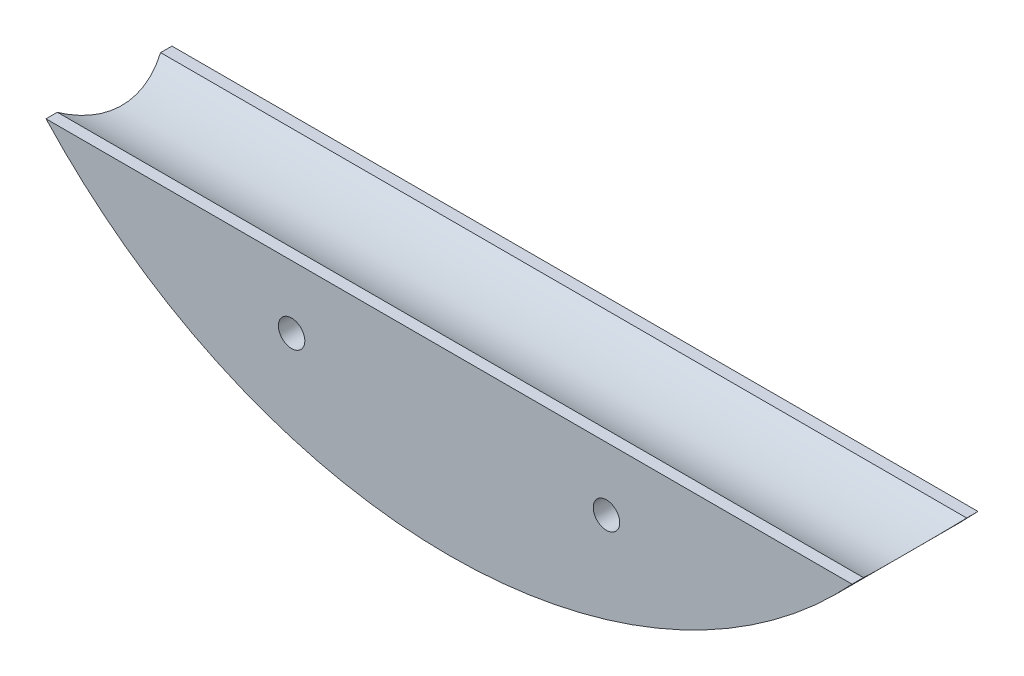
SolidWorks part; units mm, degrees
material "3.3320 (EN-AW 5019)"
ref_plane "Спереди" through (0, 0, 0) normal (0, 0, 1) x (1, 0, 0)
ref_plane "Сверху" through (0, 0, 0) normal (0, 1, 0) x (1, 0, 0)
ref_plane "Справа" through (0, 0, 0) normal (1, 0, 0) x (0, 0, -1)
sketch "Эскиз1" plane through (0, 0, 0) normal (0, 0, 1) x (1, 0, 0)
  line L0 (0, 0) -> (128, 0)
  arc A0 (0, 0) -> (128, 0) centre (64, 59) ccw
  point P4 (64, 59)
  dimension "D1" = 128
  dimension "D2" = 59
extrude "Бобышка-Вытянуть1" add sketch "Эскиз1" along normal blind 20
sketch "Эскиз2" plane through (0, 0, 0) normal (1, 0, 0) x (0, 0, -1)
  line L0 (-20, 0) -> (0, 0) construction
  circle A0 centre (-10, 14.6) radius 16.7451
  point P3 (-10, 14.6)
  point P4 (-1.8, 0)
  dimension "D1" = 14.6
  dimension "D2" = 1.8
extrude "Вырез-Вытянуть1" cut sketch "Эскиз2" along normal through all
hole_wizard "Отверстие обработанное метчиком M5x0.82" positions "Эскиз4" profile "Эскиз3" tap size "M5x0.8" standard "Ansi Metric"
sketch "Эскиз4" plane through (0, 0, 20) normal (0, 0, 1) x (1, 0, 0)
  line L0 (128, 0) -> (0, 0) construction
  point P0 (39, -10)
  point P3 (64, 0)
  dimension "D1" = 10
  dimension "D2" = 25
sketch "Эскиз3" plane through (39, -10, 20) normal (1, 0, 0) x (0, -1, 0)
  line L0 (0, 0) -> (0, 10.7618)
  line L1 (0, 10.7618) -> (2.1, 9.5)
  line L2 (2.1, 9.5) -> (2.1, 0)
  line L5 (2.1, 0) -> (0, 0)
  line L10 (0, 10.7618) -> (-2.1, 9.5) construction
  line L11 (0, -6.35) -> (0, 107.95) construction
  dimension "Диаметр сверла" = 4.2
  dimension "Глубина сверла" = 9.5
  dimension "Угол заточки сверла" = 118
cosmetic thread "Отверстие резьбы5" parameters "D1"=9.5, "D2"=5
hole_wizard "Отверстие обработанное метчиком M5x0.81" positions "Эскиз6" profile "Эскиз5" tap size "M5x0.8" standard "Ansi Metric"
sketch "Эскиз6" plane through (0, 0, 20) normal (0, 0, 1) x (1, 0, 0)
  line L0 (128, 0) -> (0, 0) construction
  point P0 (89, -10)
  point P5 (64, 0)
  dimension "D1" = 10
  dimension "D2" = 25
sketch "Эскиз5" plane through (89, -10, 20) normal (1, 0, 0) x (0, -1, 0)
  line L0 (0, 0) -> (0, 10.7618)
  line L1 (0, 10.7618) -> (2.1, 9.5)
  line L2 (2.1, 9.5) -> (2.1, 0)
  line L5 (2.1, 0) -> (0, 0)
  line L10 (0, 10.7618) -> (-2.1, 9.5) construction
  line L11 (0, -6.35) -> (0, 107.95) construction
  dimension "Диаметр сверла" = 4.2
  dimension "Глубина сверла" = 9.5
  dimension "Угол заточки сверла" = 118
cosmetic thread "Отверстие резьбы4" parameters "D1"=9.5, "D2"=5
ref_plane "Средняя плоскость" through (64, 0, 0) normal (1, 0, 0) x (0, 0, -1)
